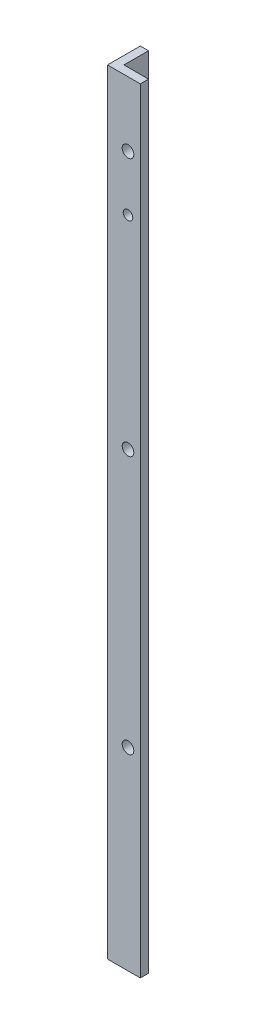
SolidWorks part; units mm, degrees
material "Alumina"
ref_plane "Front Plane" through (0, 0, 0) normal (0, 0, 1) x (1, 0, 0)
ref_plane "Top Plane" through (0, 0, 0) normal (0, 1, 0) x (1, 0, 0)
ref_plane "Right Plane" through (0, 0, 0) normal (1, 0, 0) x (0, 0, -1)
sketch "Sketch1" plane through (0, 0, 0) normal (0, 1, 0) x (1, 0, 0)
  line L0 (-13.7141, 0) -> (20.1365, 0) construction
  line L7 (0, 0) -> (12.7, 0)
  line L8 (0, 0) -> (0, 12.7)
  line L9 (3.18, 3.18) -> (12.7, 3.18)
  line L10 (3.18, 3.18) -> (3.18, 12.7)
  line L11 (0, 12.7) -> (3.18, 12.7)
  line L12 (12.7, 0) -> (12.7, 3.18)
  dimension "D1" = 12.7
  dimension "D2" = 12.7
  dimension "D3" = 3.18
extrude "Boss-Extrude1" add sketch "Sketch1" along normal blind 300
sketch "Sketch3" plane through (0, 0, -3.18) normal (0, 0, -1) x (-1, 0, 0)
  line L0 (-7.94, 300) -> (-7.94, 0) construction
  line L1 (-12.7, 300) -> (-3.18, 300) construction
  circle A2 centre (-7.94, 275) radius 2.25
  circle A6 centre (-7.94, 175) radius 2.25
  circle A7 centre (-7.94, 75) radius 2.25
  dimension "D2" = 4.5
  dimension "D1" = 25
extrude "Cut-Extrude1" cut sketch "Sketch3" against normal blind 300
sketch "Sketch6" plane through (3.18, 0, 0) normal (1, 0, 0) x (0, 0, -1)
  line L0 (7.94, 300) -> (7.94, 0) construction
  line L1 (3.18, 300) -> (12.7, 300) construction
  line L2 (3.18, 0) -> (12.7, 0) construction
  circle A0 centre (7.94, 225) radius 2.25
  circle A2 centre (7.94, 125) radius 2.25
  circle A3 centre (7.94, 25) radius 2.25
  dimension "D2" = 4.5
  dimension "D1" = 75
extrude "Cut-Extrude2" cut sketch "Sketch6" against normal blind 10
sketch "Sketch7" plane through (0, 0, 0) normal (0, 0, 1) x (1, 0, 0)
  circle A0 centre (7.94, 253.6) radius 1.85
extrude "Cut-Extrude3" cut sketch "Sketch7" against normal through all
